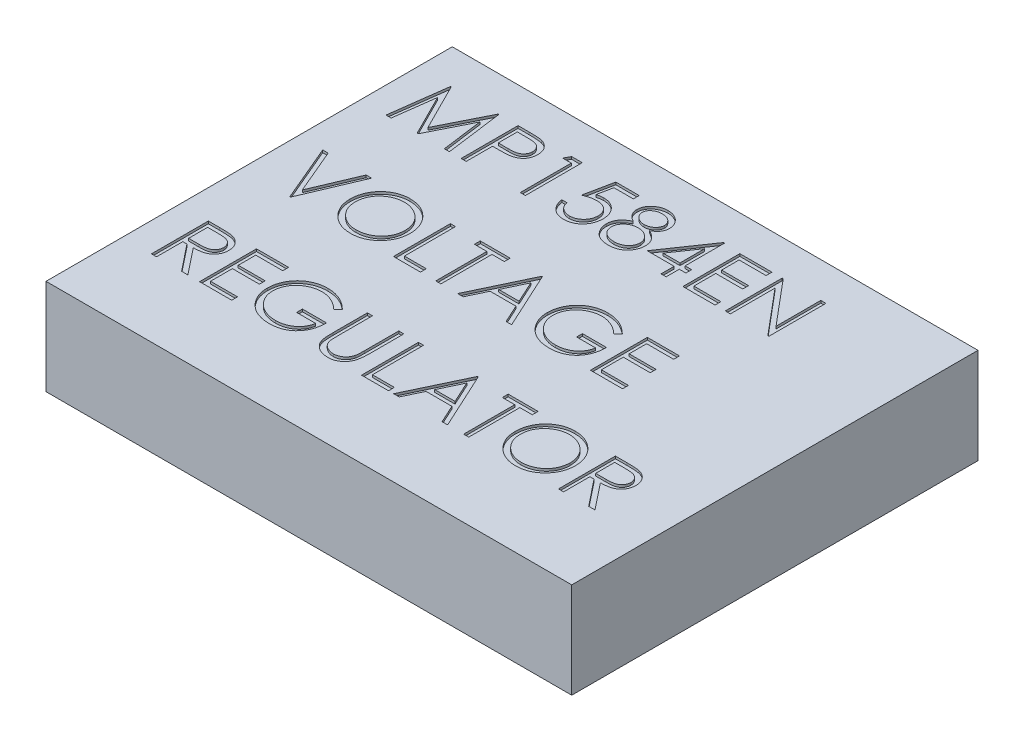
SolidWorks part; units mm, degrees
ref_plane "Front Plane" through (0, 0, 0) normal (0, 0, 1) x (1, 0, 0)
ref_plane "Top Plane" through (0, 0, 0) normal (0, 1, 0) x (1, 0, 0)
ref_plane "Right Plane" through (0, 0, 0) normal (1, 0, 0) x (0, 0, -1)
sketch "Sketch1" plane through (0, 0, 0) normal (0, 1, 0) x (1, 0, 0)
  line L1 (-11, -8.5) -> (11, -8.5)
  line L2 (-11, -8.5) -> (-11, 8.5)
  line L3 (-11, 8.5) -> (11, 8.5)
  line L4 (11, -8.5) -> (11, 8.5)
  line L5 (-11, -8.5) -> (11, 8.5) construction
  line L6 (-11, 8.5) -> (11, -8.5) construction
  point P0 (0, 0)
  dimension "D1" = 22
  dimension "D2" = 17
extrude "Boss-Extrude1" add sketch "Sketch1" along normal blind 4
sketch "Sketch2" plane through (0, 4, 0) normal (0, 1, 0) x (1, 0, 0)
  text T0 "MP1584EN\r\nVOLTAGE\r\nREGULATOR" font "Century Gothic" height in points 9
extrude "Cut-Extrude1" cut sketch "Sketch2" against normal blind 0.1
